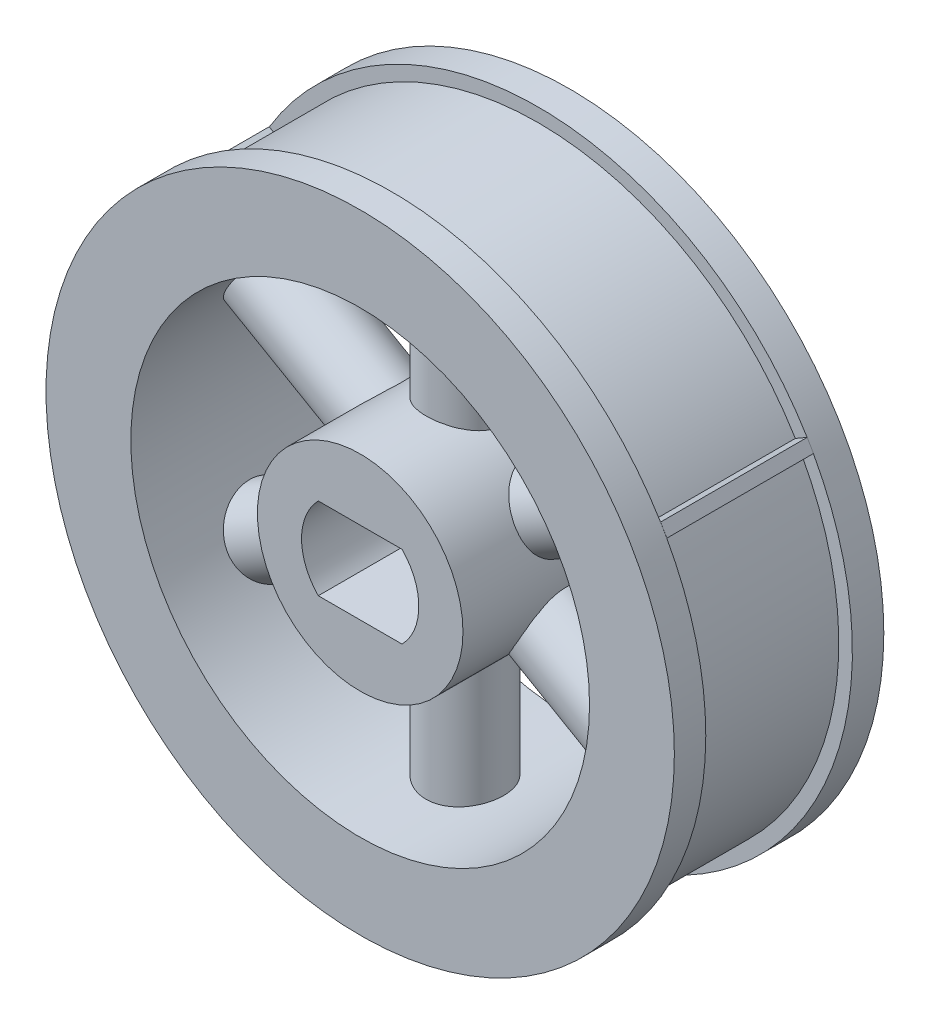
SolidWorks part; units mm, degrees
other "Markup1"
sketch "Sketch9" plane through (15, 15, 0) normal (0.4109, 0.6751, -0.6127) x (0.4132, 0.4611, 0.7853)
material "ABS"
ref_plane "Front Plane" through (0, 0, 0) normal (0, 0, 1) x (1, 0, 0)
ref_plane "Top Plane" through (0, 0, 0) normal (0, 1, 0) x (1, 0, 0)
ref_plane "Right Plane" through (0, 0, 0) normal (1, 0, 0) x (0, 0, -1)
sketch "Sketch2" plane through (0, 0, 0) normal (0, 0, 1) x (1, 0, 0)
  line L0 (2, 1.9596) -> (-2, 1.9596)
  line L1 (2.8, 0) -> (-2.8, 0) construction
  line L3 (2, -1.9596) -> (-2, -1.9596)
  circle A0 centre (0, 0) radius 2.8
  circle A1 centre (0, 0) radius 15
  circle A2 centre (0, 0) radius 4.9074
  circle A3 centre (0, 0) radius 14.35
extrude "Boss-Extrude1" add sketch "Sketch2" along normal blind 10 contours A2 A0 | L3 A0 | L0 A0
sketch "Sketch3" plane through (0, 0, 0) normal (0, 0, 1) x (1, 0, 0)
  circle A0 centre (0, 0) radius 14.35
  circle A1 centre (0, 0) radius 15
  circle A2 centre (0, 0) radius 2.8
  circle A3 centre (0, 0) radius 10.9501
extrude "Boss-Extrude2" add sketch "Sketch3" along normal blind 10 separate body contours A0 A3
sketch "Sketch4" plane through (0, 0, 0) normal (0, 0, 1) x (1, 0, 0)
  circle A0 centre (0, 0) radius 14.35
  circle A1 centre (0, 0) radius 15
extrude "Boss-Extrude3" add sketch "Sketch4" along normal blind 1.5
sketch "Sketch5" plane through (0, 0, 10) normal (0, 0, 1) x (1, 0, 0)
  circle A0 centre (0, 0) radius 14.35
  circle A1 centre (0, 0) radius 15
extrude "Boss-Extrude4" add sketch "Sketch5" against normal blind 1.5
ref_plane "Plane1" through (0, 2.9596, 0) normal (0, -1, 0) x (-1, 0, 0)
sketch "Sketch7" plane through (0, 2.9596, 0) normal (0, -1, 0) x (-1, 0, 0)
  line L0 (0, 0) -> (0, -10)
  line L1 (-15, -10) -> (15, -10) construction
  circle A0 centre (0, -5) radius 1.8546
extrude "Boss-Extrude5" add sketch "Sketch7" against normal blind 8.5 contours L0 A0 | L0 A0
pattern_circular "CirPattern1" count 6 over 360 about axis through (0, 0, 10) along (0, 0, 1) of "Boss-Extrude5"
ref_plane "Plane2" through (0, 0, 1.5) normal (0, 0, 1) x (1, 0, 0)
sketch "Sketch8" plane through (0, 0, 1.5) normal (0, 0, 1) x (1, 0, 0)
  line L0 (0, -14.35) -> (0, -15)
  line L2 (-0.299, -15.0031) -> (0.299, -15.0031)
  line L3 (-0.299, -15.0031) -> (-0.299, -14.3469)
  line L4 (-0.299, -14.3469) -> (0.299, -14.3469)
  line L5 (0.299, -15.0031) -> (0.299, -14.3469)
  line L6 (-0.299, -15.0031) -> (0.299, -14.3469) construction
  line L7 (-0.299, -14.3469) -> (0.299, -15.0031) construction
  circle A0 centre (0, 0) radius 14.35 construction
  circle A3 centre (0, 0) radius 15 construction
  point P2 (0, -14.675)
  point P6 (0, -14.35)
extrude "Boss-Extrude6" add sketch "Sketch8" along normal up to surface (7 mm away) up to face at (14.35, 0, 8.5)
pattern_circular "CirPattern2" count 3 over 360 about axis through (0, 0, 0) along (0, 0, 1) of "Boss-Extrude6"
